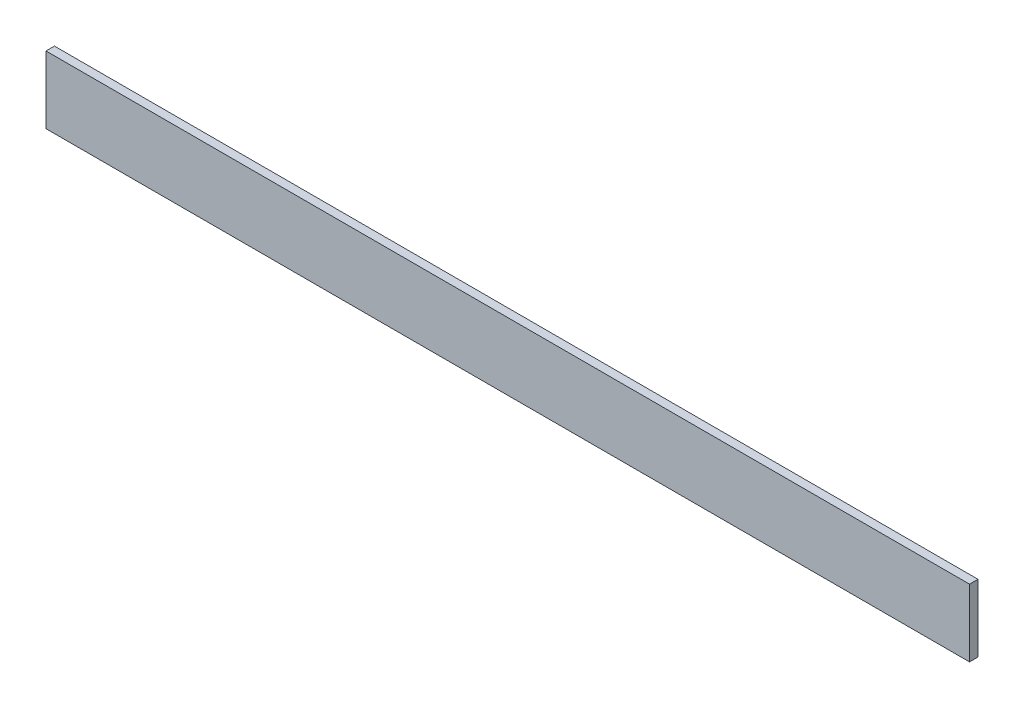
SolidWorks part; units mm, degrees
ref_plane "Front Plane" through (0, 0, 0) normal (0, 0, 1) x (1, 0, 0)
ref_plane "Top Plane" through (0, 0, 0) normal (0, 1, 0) x (1, 0, 0)
ref_plane "Right Plane" through (0, 0, 0) normal (1, 0, 0) x (0, 0, -1)
sketch "Sketch1" plane through (0, 0, 0) normal (0, 0, 1) x (1, 0, 0)
  line L1 (-82.55, 25.4) -> (527.05, 25.4)
  line L2 (-82.55, 25.4) -> (-82.55, -19.05)
  line L3 (-82.55, -19.05) -> (527.05, -19.05)
  line L4 (527.05, 25.4) -> (527.05, -19.05)
  dimension "D1" = 44.45
  dimension "D2" = 609.6
extrude "Boss-Extrude1" add sketch "Sketch1" along normal blind 5.588
equation "\"width\"= 9in"
equation "\"Height\"= 18in"
equation "\"thick\"= 0.22"
equation "\"D1@Boss-Extrude1\"=\"thick\""
